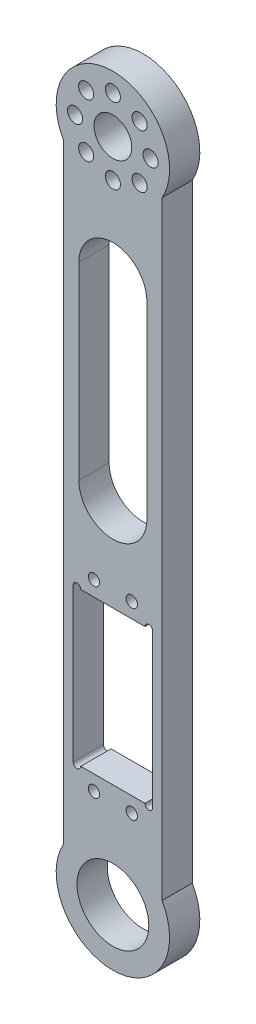
SolidWorks part; units mm, degrees
material "1060 合金"
ref_plane "前视基准面" through (0, 0, 0) normal (0, 0, 1) x (1, 0, 0)
ref_plane "上视基准面" through (0, 0, 0) normal (0, 1, 0) x (1, 0, 0)
ref_plane "右视基准面" through (0, 0, 0) normal (1, 0, 0) x (0, 0, -1)
sketch "草图1" plane through (0, 0, 0) normal (0, 0, 1) x (1, 0, 0)
  line L1 (-13, 88) -> (13, 88)
  line L2 (-13, 88) -> (-13, -88)
  line L3 (-13, -88) -> (13, -88)
  line L4 (13, 88) -> (13, -88)
  line L5 (-13, 88) -> (13, -88) construction
  line L6 (-13, -88) -> (13, 88) construction
  circle A0 centre (0, -88) radius 15
  circle A1 centre (0, 88) radius 15
  point P0 (0, 0)
  dimension "D3" = 30
  dimension "D4" = 30
  dimension "D1" = 176
  dimension "D2" = 26
extrude "凸台-拉伸1" add sketch "草图1" along normal blind 8 contours A1 L2 A0 L4 | L2 A1 L4 L1 | L4 A1 L2 L1 | L2 A0 L4 L3 | L4 A0 L2 L3
sketch "草图2" plane through (0, 0, 8) normal (0, 0, 1) x (1, 0, 0)
  line L0 (10, 88) -> (0, 88) construction
  line L1 (0, 88) -> (7.0711, 95.0711) construction
  circle A0 centre (0, 88) radius 5
  circle A1 centre (0, 88) radius 10 construction
  circle A2 centre (0, 98) radius 2
  circle A3 centre (10, 88) radius 2
  circle A4 centre (0, 78) radius 2
  circle A5 centre (-10, 88) radius 2
  circle A6 centre (0, -88) radius 9.5
  circle A7 centre (7.0711, 95.0711) radius 2
  circle A8 centre (7.0711, 80.9289) radius 2
  circle A9 centre (-7.0711, 80.9289) radius 2
  circle A10 centre (-7.0711, 95.0711) radius 2
  point P15 (0, 88)
  point P27 (0, 88)
  dimension "D1" = 10
  dimension "D2" = 20
  dimension "D3" = 4
  dimension "D5" = 19
  dimension "D7" = 4
  dimension "D6" = 45
  dimension "D4" = 4
  dimension "D8" = 4
extrude "切除-拉伸1" cut sketch "草图2" against normal blind 8
sketch "草图3" plane through (0, 0, 8) normal (0, 0, 1) x (1, 0, 0)
  line L0 (13, 80.5167) -> (13, -80.5167) construction
  line L1 (-10.5, -20) -> (10.5, -20)
  line L2 (-10.5, -20) -> (-10.5, -60.5)
  line L3 (-10.5, -60.5) -> (10.5, -60.5)
  line L4 (10.5, -20) -> (10.5, -60.5)
  line L5 (-10.5, -20) -> (10.5, -60.5) construction
  line L6 (-10.5, -60.5) -> (10.5, -20) construction
  circle A0 centre (0, -88) radius 9.5 construction
  point P0 (0, -40.25)
  dimension "D1" = 40.5
  dimension "D2" = 21
  dimension "D3" = 27.5
  dimension "D4" = 2.5
extrude "切除-拉伸2" cut sketch "草图3" against normal blind 10
sketch "草图4" plane through (0, 0, 8) normal (0, 0, 1) x (1, 0, 0)
  line L0 (13, 80.5167) -> (13, -80.5167) construction
  line L1 (-13, 80.5167) -> (-13, -80.5167) construction
  line L2 (-10.5, -60.5) -> (10.5, -60.5) construction
  line L3 (10.5, -20) -> (-10.5, -20) construction
  circle A0 centre (-5, -16) radius 1.5
  circle A1 centre (5, -16) radius 1.5
  circle A2 centre (-5, -64.5) radius 1.5
  circle A3 centre (5, -64.5) radius 1.5
  dimension "D1" = 3
  dimension "D2" = 3
  dimension "D3" = 3
  dimension "D4" = 3
  dimension "D5" = 8
  dimension "D6" = 10
  dimension "D7" = 8
  dimension "D8" = 4
  dimension "D9" = 8
  dimension "D10" = 10
  dimension "D11" = 8
  dimension "D12" = 4
extrude "切除-拉伸3" cut sketch "草图4" against normal blind 10
sketch "草图5" plane through (0, 0, 8) normal (0, 0, 1) x (1, 0, 0)
  line L0 (10.5, -20) -> (-10.5, -20) construction
  line L1 (-10.5, -20) -> (-10.5, -60.5) construction
  line L2 (0, -20) -> (0, -60.5) construction
  line L3 (-10.5, -60.5) -> (10.5, -60.5) construction
  line L4 (-10.5, -40.25) -> (10.5, -40.25) construction
  line L5 (10.5, -60.5) -> (10.5, -20) construction
  circle A0 centre (-9.5, -20) radius 1
  circle A1 centre (9.5, -20) radius 1
  circle A2 centre (9.5, -60.5) radius 1
  circle A3 centre (-9.5, -60.5) radius 1
  dimension "D1" = 2
  dimension "D2" = 1
extrude "切除-拉伸4" cut sketch "草图5" against normal blind 10
sketch "草图6" plane through (0, 0, 8) normal (0, 0, 1) x (1, 0, 0)
  line L0 (13, 80.5167) -> (13, -80.5167) construction
  line L1 (-9, 54.75) -> (9, 54.75)
  line L2 (-9, 54.75) -> (-9, 4.75)
  line L3 (-9, 4.75) -> (9, 4.75)
  line L4 (9, 54.75) -> (9, 4.75)
  line L5 (-9, 54.75) -> (9, 4.75) construction
  line L6 (-9, 4.75) -> (9, 54.75) construction
  circle A0 centre (5, -16) radius 1.5 construction
  arc A2 (-9, 4.75) -> (9, 4.75) centre (0, 4.75) ccw
  arc A3 (-9, 54.75) -> (9, 54.75) centre (0, 54.75) cw
  point P0 (0, 29.75)
  dimension "D1" = 50
  dimension "D2" = 18
  dimension "D3" = 20.75
  dimension "D4" = 4
extrude "切除-拉伸5" cut sketch "草图6" against normal blind 10 contours A3 L1 | L4 L1 L2 L3 | L3 A2
